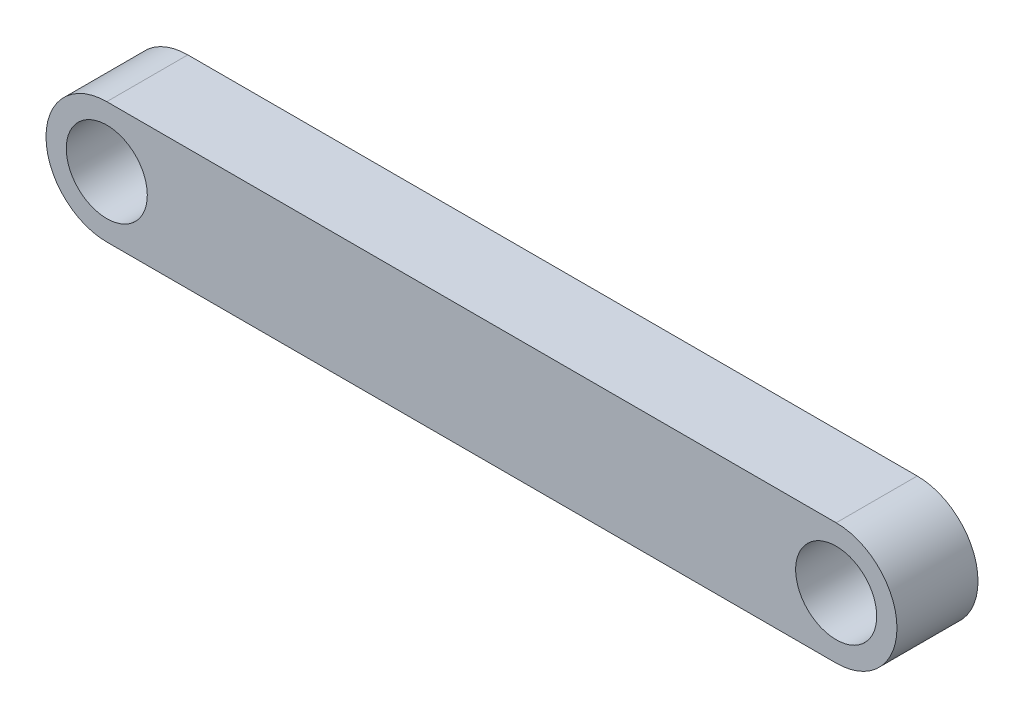
SolidWorks part; units mm, degrees
ref_plane "Front Plane" through (0, 0, 0) normal (0, 0, 1) x (1, 0, 0)
ref_plane "Top Plane" through (0, 0, 0) normal (0, 1, 0) x (1, 0, 0)
ref_plane "Right Plane" through (0, 0, 0) normal (1, 0, 0) x (0, 0, -1)
sketch "Sketch1" plane through (0, 0, 0) normal (0, 0, 1) x (1, 0, 0)
  line L0 (-17.8588, 0) -> (-15.8588, 0) construction
  line L1 (-17.8588, 3) -> (18.1412, 3)
  line L2 (-17.8588, -3) -> (18.1412, -3)
  arc A0 (-17.8588, 3) -> (-17.8588, -3) centre (-17.8588, 0) ccw
  circle A1 centre (-17.8588, 0) radius 2
  arc A2 (18.1412, -3) -> (18.1412, 3) centre (18.1412, 0) ccw
  circle A3 centre (18.1412, 0) radius 2
  dimension "D2" = 6
  dimension "D3" = 4
  dimension "D4" = 6
  dimension "D5" = 4
  dimension "D1" = 36
extrude "Boss-Extrude1" add sketch "Sketch1" along normal blind 4
